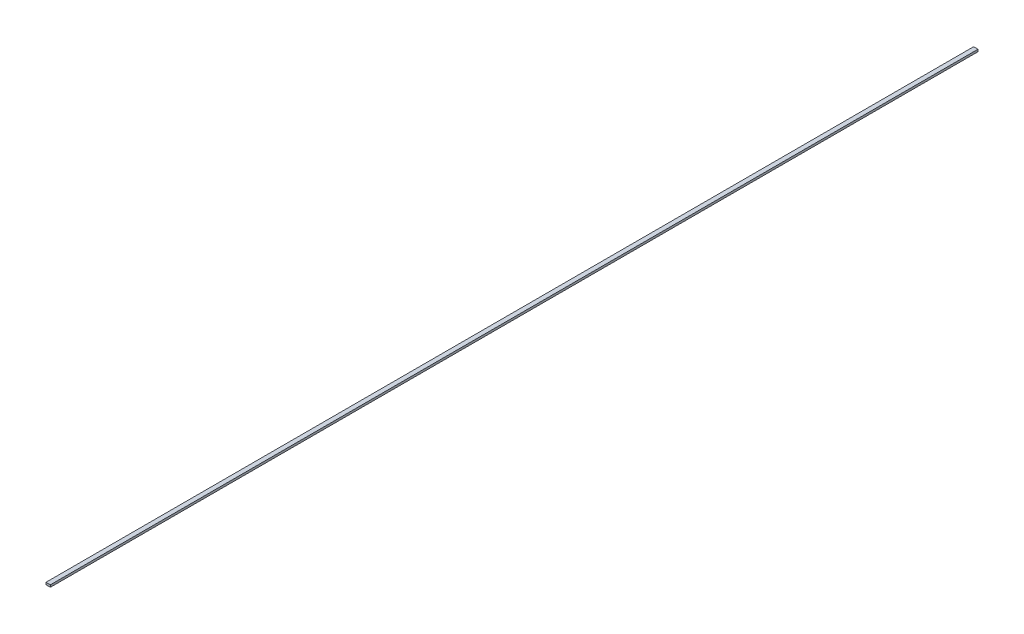
SolidWorks part; units mm, degrees
ref_plane "Front Plane" through (0, 0, 0) normal (0, 0, 1) x (1, 0, 0)
ref_plane "Top Plane" through (0, 0, 0) normal (0, 1, 0) x (1, 0, 0)
ref_plane "Right Plane" through (0, 0, 0) normal (1, 0, 0) x (0, 0, -1)
sketch "Sketch1" plane through (0, 0, 0) normal (0, 0, 1) x (1, 0, 0)
  line L1 (0, 0) -> (5, 0)
  line L2 (0, 0) -> (0, 2.5)
  line L3 (0, 2.5) -> (5, 2.5)
  line L4 (5, 0) -> (5, 2.5)
  dimension "D1" = 5
  dimension "D2" = 2.5
extrude "Boss-Extrude1" add sketch "Sketch1" along normal blind 1060
